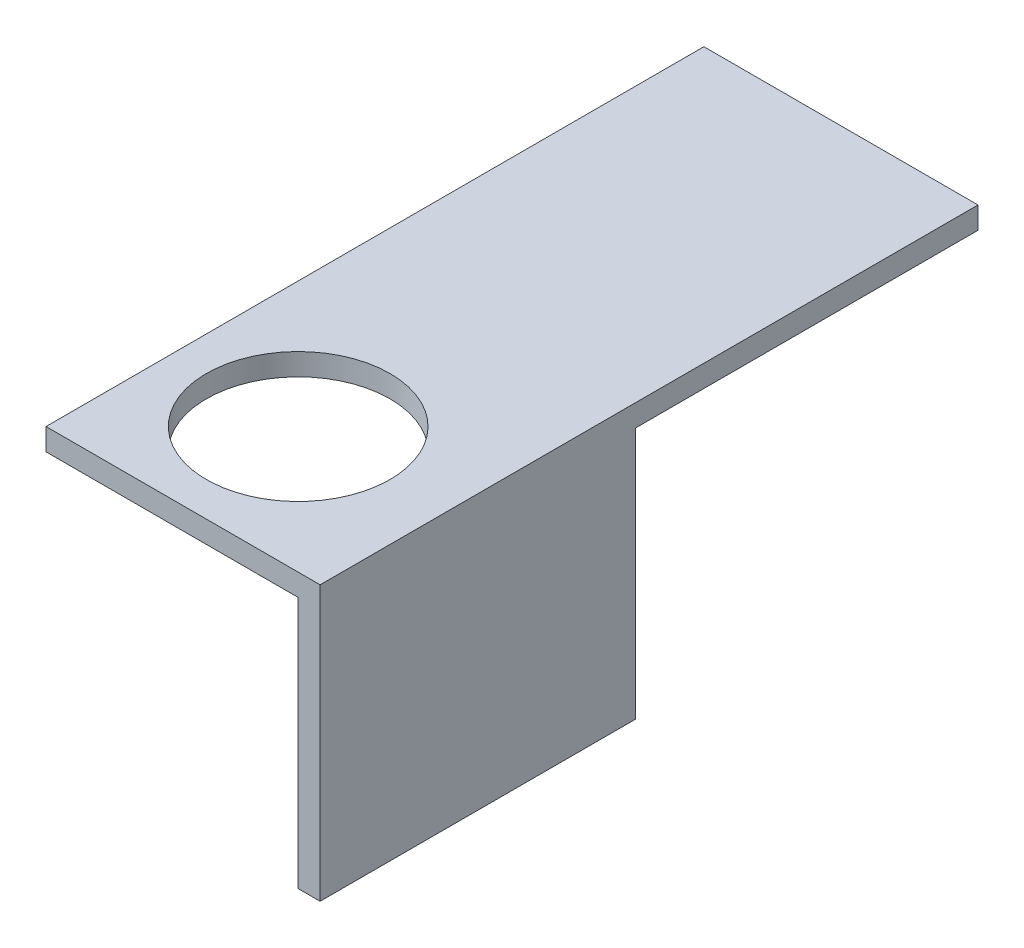
SolidWorks part; units mm, degrees
ref_plane "Alzado" through (0, 0, 0) normal (0, 0, 1) x (1, 0, 0)
ref_plane "Planta" through (0, 0, 0) normal (0, 1, 0) x (1, 0, 0)
ref_plane "Vista lateral" through (0, 0, 0) normal (1, 0, 0) x (0, 0, -1)
sketch "Croquis1" plane through (0, 0, 0) normal (0, 0, 1) x (1, 0, 0)
  line L0 (-124.6107, 44.964) -> (-74.6107, 44.964)
  line L1 (-74.6107, 44.964) -> (-74.6107, -5.036)
  line L2 (-124.6107, 44.964) -> (-124.6107, 40.964)
  line L3 (-124.6107, 40.964) -> (-78.6107, 40.964)
  line L4 (-78.6107, 40.964) -> (-78.6107, -5.036)
  line L5 (-78.6107, -5.036) -> (-74.6107, -5.036)
  dimension "D1" = 50
  dimension "D2" = 50
  dimension "D3" = 4
  dimension "D4" = 4
extrude "Saliente-Extruir1" add sketch "Croquis1" along normal blind 120
sketch "Croquis2" plane through (-78.6107, 0, 0) normal (-1, 0, 0) x (0, 0, 1)
  line L0 (0, 40.964) -> (62.5, 40.964)
  line L1 (120, 40.964) -> (0, 40.964) construction
  line L2 (0, 40.964) -> (0, -5.036)
  line L4 (120, -5.036) -> (0, -5.036) construction
  line L5 (62.5, 40.964) -> (62.5, -5.036)
  line L6 (62.5, -5.036) -> (0, -5.036)
  dimension "D1" = 62.5
extrude "Cortar-Extruir4" cut sketch "Croquis2" along normal blind 118 and the other way blind 26 contours L6 L2 L0 L5
sketch "Croquis3" plane through (0, 40.964, 0) normal (0, -1, 0) x (1, 0, 0)
  line L0 (-124.6107, 120) -> (-124.6107, 0) construction
  circle A0 centre (-101.6107, 97) radius 16.7529
  dimension "D1" = 23
  dimension "D2" = 33.5057
extrude "Cortar-Extruir10" cut sketch "Croquis3" along normal blind 30 and the other way blind 41
